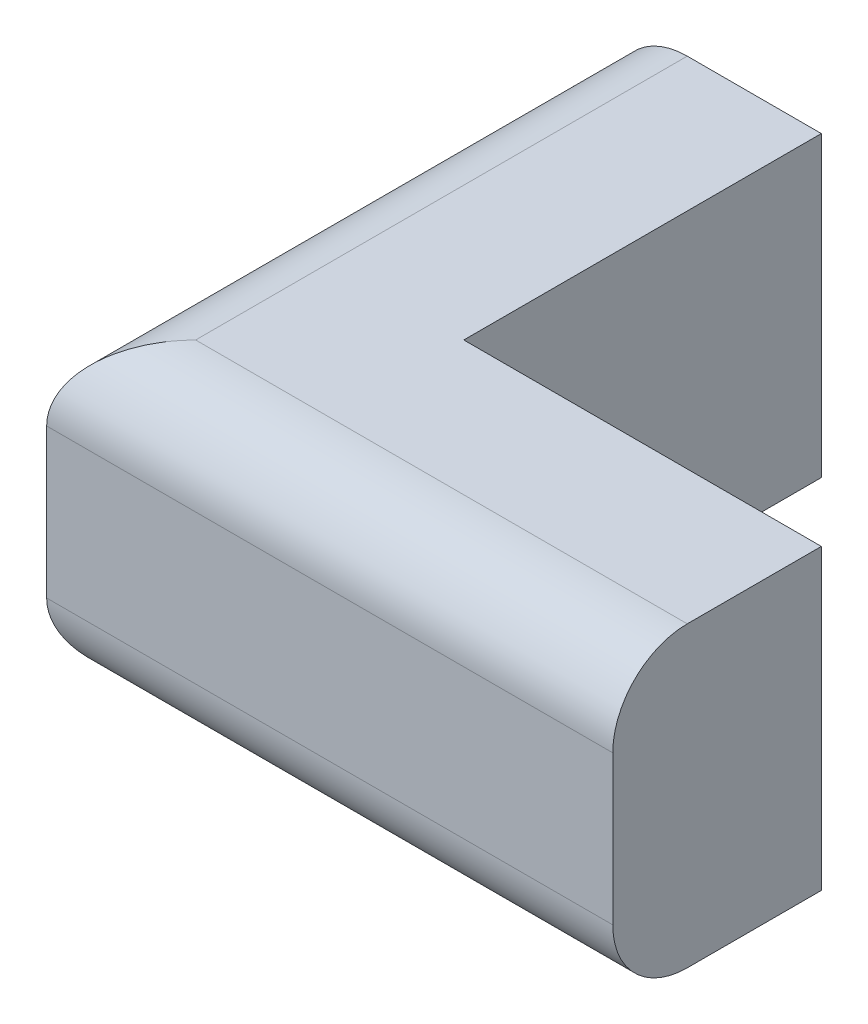
SolidWorks part; units mm, degrees
ref_plane "Front Plane" through (0, 0, 0) normal (0, 0, 1) x (1, 0, 0)
ref_plane "Top Plane" through (0, 0, 0) normal (0, 1, 0) x (1, 0, 0)
ref_plane "Right Plane" through (0, 0, 0) normal (1, 0, 0) x (0, 0, -1)
sketch "Sketch1" plane through (0, 0, 0) normal (0, 1, 0) x (1, 0, 0)
  line L0 (88.9, 241.3) -> (88.9, 88.9)
  line L1 (0, 0) -> (241.3, 0)
  line L2 (0, 0) -> (0, 241.3)
  line L3 (0, 241.3) -> (241.3, 241.3)
  line L4 (241.3, 0) -> (241.3, 241.3)
  line L5 (88.9, 88.9) -> (241.3, 88.9)
  dimension "D1" = 241.3
  dimension "D2" = 241.3
  dimension "D3" = 152.4
  dimension "D4" = 152.4
extrude "Boss-Extrude1" add sketch "Sketch1" along normal blind 127 contours L5 L0 L3 L2 L1 L4
fillet "Fillet1" radius 31.75 4 edges at (0, 0, -120.65) (120.65, 0, 0) (0, 127, -120.65) (120.65, 127, 0)
